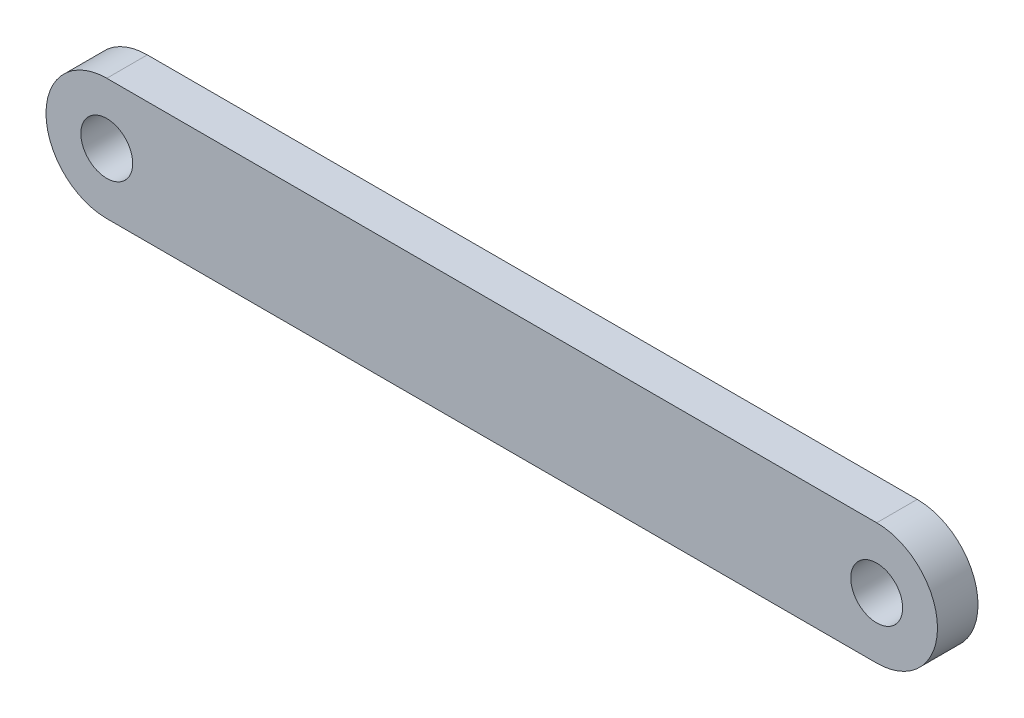
SolidWorks part; units mm, degrees
ref_plane "Front Plane" through (0, 0, 0) normal (0, 0, 1) x (1, 0, 0)
ref_plane "Top Plane" through (0, 0, 0) normal (0, 1, 0) x (1, 0, 0)
ref_plane "Right Plane" through (0, 0, 0) normal (1, 0, 0) x (0, 0, -1)
sketch "Sketch1" plane through (0, 0, 0) normal (0, 0, 1) x (1, 0, 0)
  line L0 (0, 0) -> (60.325, 0) construction
  line L1 (0, 4.7625) -> (60.325, 4.7625)
  line L2 (0, -4.7625) -> (60.325, -4.7625)
  arc A0 (0, 4.7625) -> (0, -4.7625) centre (0, 0) ccw
  arc A1 (60.325, -4.7625) -> (60.325, 4.7625) centre (60.325, 0) ccw
  circle A2 centre (0, 0) radius 2.032
  circle A3 centre (60.325, 0) radius 2.032
  point P3 (30.1625, 0)
  dimension "D2" = 4.7625
  dimension "D3" = 4.064
  dimension "D1" = 60.325
extrude "Boss-Extrude1" add sketch "Sketch1" along normal blind 3.175
